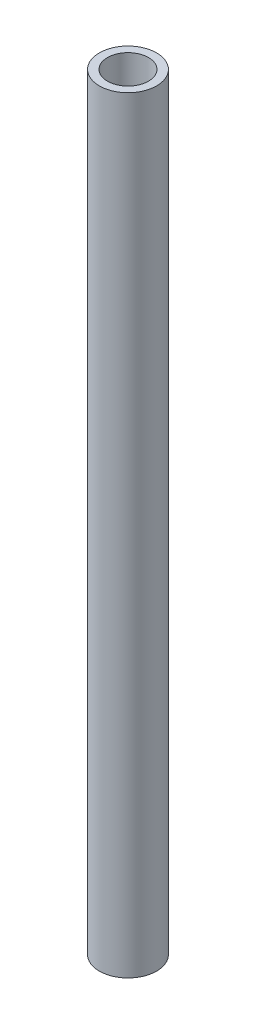
SolidWorks part; units mm, degrees
ref_plane "Front Plane" through (0, 0, 0) normal (0, 0, 1) x (1, 0, 0)
ref_plane "Top Plane" through (0, 0, 0) normal (0, 1, 0) x (1, 0, 0)
ref_plane "Right Plane" through (0, 0, 0) normal (1, 0, 0) x (0, 0, -1)
sketch "Sketch1" plane through (0, 0, 0) normal (0, 1, 0) x (1, 0, 0)
  circle A0 centre (0, 0) radius 7.6454
  circle A1 centre (0, 0) radius 10.668
  dimension "D1" = 21.336
  dimension "D2" = 15.2908
extrude "Boss-Extrude1" add sketch "Sketch1" along normal blind 285.75
ref_plane "Plane1" through (0, 142.875, 0) normal (0, 1, 0) x (1, 0, 0)
ref_plane "Plane2" through (0, 285.75, 0) normal (0, 1, 0) x (1, 0, 0)
